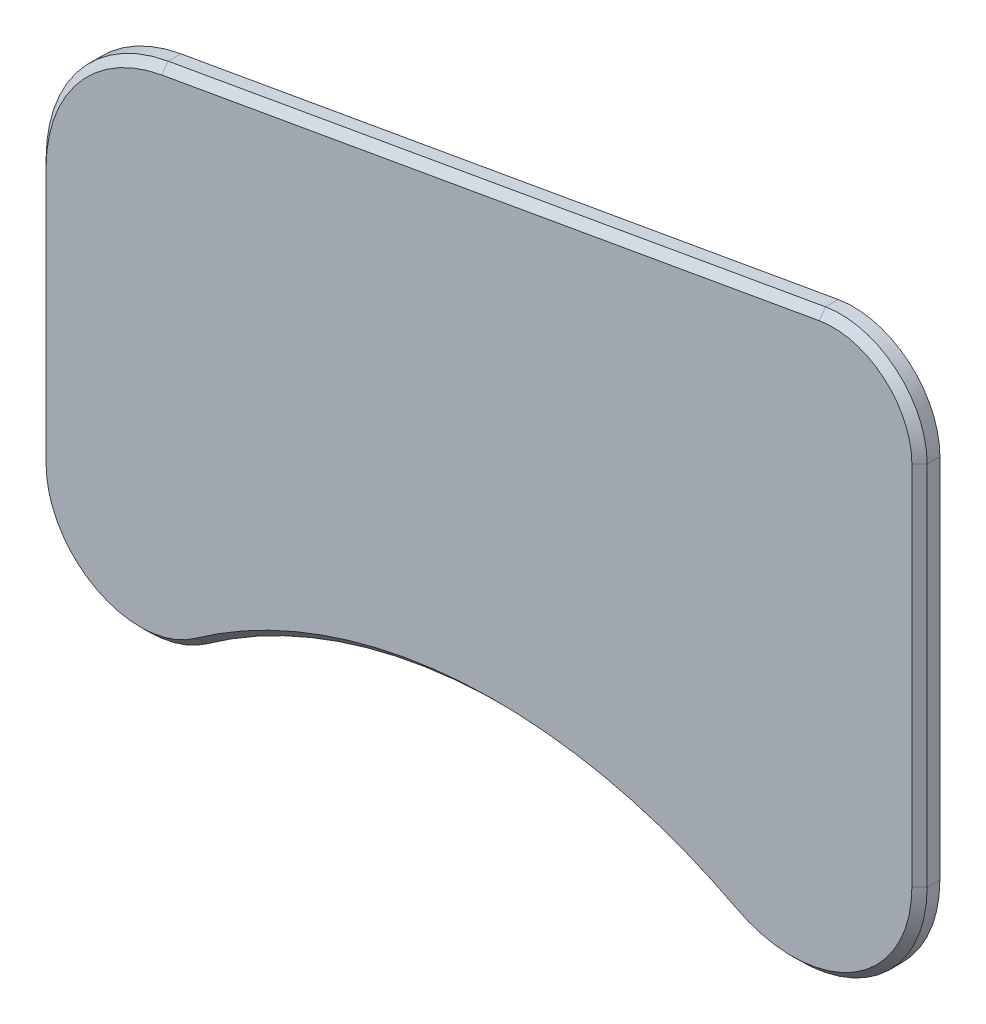
SolidWorks part; units mm, degrees
ref_plane "Front Plane" through (0, 0, 0) normal (0, 0, 1) x (1, 0, 0)
ref_plane "Top Plane" through (0, 0, 0) normal (0, 1, 0) x (1, 0, 0)
ref_plane "Right Plane" through (0, 0, 0) normal (1, 0, 0) x (0, 0, -1)
sketch "Sketch1" plane through (0, 0, 0) normal (0, 0, 1) x (1, 0, 0)
  line L3 (70.048, 42.7987) -> (-59.0358, 20.0378)
  line L4 (-83, -8.5217) -> (-83, -58.9217)
  line L5 (90, -45.9217) -> (90, 26.057)
  line L6 (70.048, 42.7987) -> (-59.0358, 20.0378)
  line L7 (-83, -8.5217) -> (-83, -58.9217)
  line L8 (90, -45.9217) -> (90, 26.057)
  arc A5 (-59.0358, 20.0378) -> (-83, -8.5217) centre (-54, -8.5217) ccw
  arc A6 (-83, -58.9217) -> (-51.3684, -75.1915) centre (-63, -58.9217) ccw
  arc A7 (53.3579, -68.0454) -> (-51.3684, -75.1915) centre (6.7894, -156.5405) ccw
  arc A8 (53.3579, -68.0454) -> (90, -45.9217) centre (65, -45.9217) ccw
  arc A9 (90, 26.057) -> (70.048, 42.7987) centre (73, 26.057) ccw
  arc A10 (-59.0358, 20.0378) -> (-83, -8.5217) centre (-54, -8.5217) ccw
  arc A11 (-83, -58.9217) -> (-51.3684, -75.1915) centre (-63, -58.9217) ccw
  arc A12 (53.3579, -68.0454) -> (-51.3684, -75.1915) centre (6.7894, -156.5405) ccw
  arc A13 (53.3579, -68.0454) -> (90, -45.9217) centre (65, -45.9217) ccw
  arc A14 (90, 26.057) -> (70.048, 42.7987) centre (73, 26.057) ccw
  dimension "D1" = 0
extrude "Boss-Extrude1" add sketch "Sketch1" along normal blind 4
chamfer "Chamfer1" distance 1.5 angle 45 8 edges at (-0.0183, -56.7725, 4) (77.9218, -67.3232, 4) (-72.1479, -76.7069, 4) (90, -9.9323, 4) (-83, -33.7217, 4) (83.9274, 39.0797, 4) (-76.2153, 10.1192, 4) (5.5061, 31.4182, 4)
